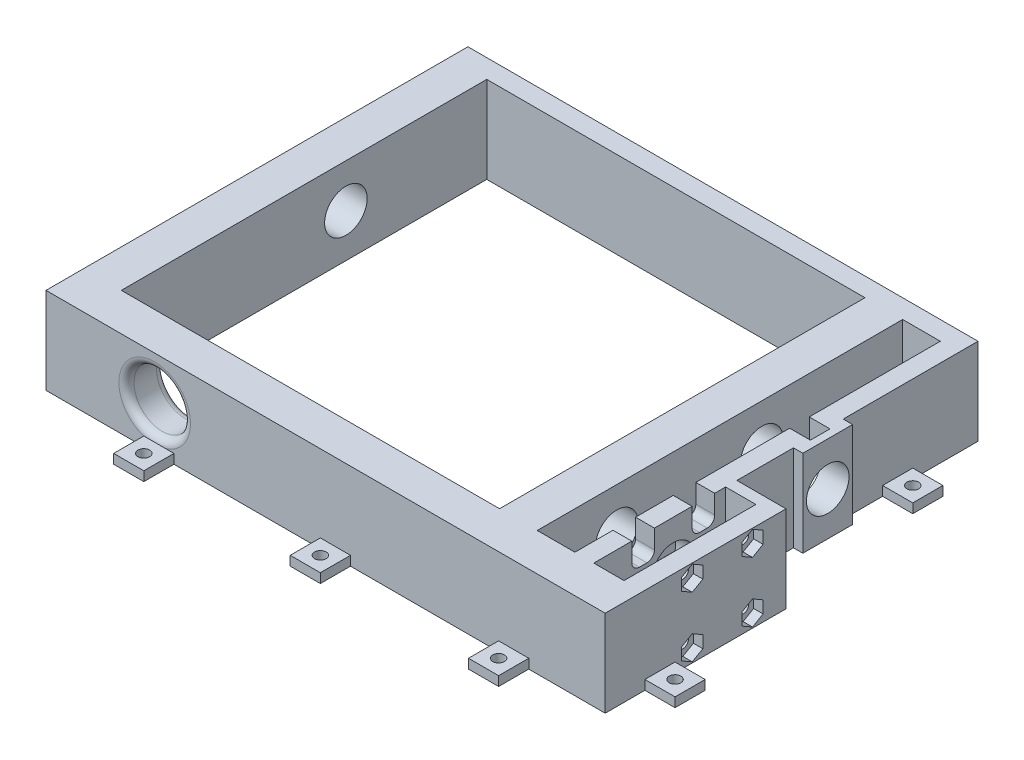
SolidWorks part; units mm, degrees
ref_plane "Front Plane" through (0, 0, 0) normal (0, 0, 1) x (1, 0, 0)
ref_plane "Top Plane" through (0, 0, 0) normal (0, 1, 0) x (1, 0, 0)
ref_plane "Right Plane" through (0, 0, 0) normal (1, 0, 0) x (0, 0, -1)
sketch "Sketch1" plane through (0, 0, 0) normal (0, 1, 0) x (1, 0, 0)
  line L0 (-50, -27.5) -> (-50, 27.5) construction
  line L1 (-40, -17.5) -> (40, -17.5) construction
  line L2 (-40, -17.5) -> (-40, 17.5) construction
  line L3 (-40, 17.5) -> (40, 17.5) construction
  line L4 (40, -17.5) -> (40, 17.5) construction
  line L5 (-40, -17.5) -> (40, 17.5) construction
  line L6 (-40, 17.5) -> (40, -17.5) construction
  line L7 (-50, 27.5) -> (50, 27.5) construction
  line L8 (50, -27.5) -> (50, 27.5) construction
  line L9 (-50, -27.5) -> (50, -27.5) construction
  line L10 (50, 0) -> (50.2, 0) construction
  line L11 (-50, 0) -> (-50.2, 0) construction
  line L12 (50.2, 0) -> (50.2, -27.5)
  line L13 (50.2, -27.5) -> (50.2, -47.5)
  line L14 (-50.2, 0) -> (-50.2, -27.5)
  line L15 (-50.2, -27.5) -> (-50.2, -47.5)
  line L16 (-50.2, -47.5) -> (50.2, -47.5)
  line L17 (50.2, 0) -> (50.2, 54.5)
  line L18 (-50.2, 0) -> (-50.2, 54.5)
  line L19 (-60.2, 0) -> (-60.2, 54.5)
  line L20 (-60.2, 0) -> (-60.2, -27.5)
  line L21 (-60.2, -27.5) -> (-60.2, -57.5)
  line L22 (-60.2, -57.5) -> (60.2, -57.5)
  line L23 (60.2, -27.5) -> (60.2, -57.5) construction
  line L24 (60.2, 0) -> (60.2, -27.5)
  line L25 (60.2, 0) -> (60.2, 54.5)
  line L26 (-50.2, 54.5) -> (-60.2, 54.5)
  line L27 (50.2, 54.5) -> (60.2, 54.5)
  line L28 (83.24, -47.5) -> (83.24, -9.5)
  line L29 (60.2, -57.5) -> (83.24, -57.5)
  line L31 (60.2, -47.5) -> (83.24, -47.5)
  line L32 (83.24, -57.5) -> (83.24, -47.5) construction
  line L33 (83.24, -57.5) -> (88.24, -57.5)
  line L34 (83.24, -57.5) -> (83.24, -9.5) construction
  line L35 (83.24, -9.5) -> (88.24, -9.5)
  line L36 (88.24, -57.5) -> (88.24, -9.5)
  line L37 (60.2, -47.5) -> (60.2, 54.5)
  line L39 (70.2, -47.5) -> (75.2, -47.5)
  line L40 (70.2, -47.5) -> (70.2, -9.5)
  line L41 (70.2, -9.5) -> (75.2, -9.5) construction
  line L42 (75.2, -47.5) -> (75.2, -9.5)
  line L43 (75.2, -9.5) -> (83.24, -9.5)
  line L44 (75.2, -9.5) -> (75.2, -12.5)
  line L45 (75.2, -12.5) -> (83.24, -12.5)
  line L46 (83.24, -9.5) -> (83.24, -12.5)
  line L47 (70.2, -9.5) -> (75.2, -9.5) construction
  line L48 (70.2, -9.5) -> (70.2, 54.5)
  line L49 (70.2, 54.5) -> (75.2, 54.5)
  line L50 (75.2, -9.5) -> (75.2, 54.5)
  line L51 (-50.2, 54.5) -> (50.2, 54.5)
  line L52 (-50.2, 54.5) -> (-50.2, 49.5)
  line L53 (-50.2, 49.5) -> (50.2, 49.5)
  line L54 (50.2, 54.5) -> (50.2, 49.5)
  line L55 (60.2, 54.5) -> (70.2, 54.5)
  line L56 (60.2, 54.5) -> (60.2, 49.5)
  line L57 (60.2, 49.5) -> (70.2, 49.5)
  line L58 (70.2, 54.5) -> (70.2, 49.5)
  point P0 (0, 0)
  point P10 (50, 0)
  point P11 (0, -27.5)
  point P12 (0, 27.5)
  point P13 (-50, 0)
  dimension "D1" = 80
  dimension "D2" = 35
  dimension "D4" = 0.2
  dimension "D5" = 20
  dimension "D7" = 8.04
  dimension "D8" = 5
  dimension "D9" = 10
  dimension "D10" = 5
  dimension "D11" = 38
  dimension "D12" = 3
  dimension "D13" = 22
  dimension "D14" = 5
  dimension "D3" = 10
  dimension "D6" = 10
extrude "Boss-Extrude1" add sketch "Sketch1" along normal mid plane 23 contours L31 L37 L24 L25 L27 L17 L12 L13 L16 L15 L14 L18 L26 L19 L20 L21 L22 L29 L33 L36 L35 L28 | L31 L42 L41 L40 | L42 L45 L28 L43 | L18 L53 L17 L51 | L37 L57 L48 L55
sketch "Sketch2" plane through (60.2, 0, 0) normal (1, 0, 0) x (0, 0, -1)
  line L4 (-47.5, -11.5) -> (49.5, -11.5)
  line L5 (49.5, -11.5) -> (49.5, 11.5)
  line L6 (-47.5, -11.5) -> (49.5, -11.5)
  line L7 (49.5, 11.5) -> (-47.5, 11.5)
  line L12 (49.5, -11.5) -> (49.5, 11.5)
  line L14 (49.5, 11.5) -> (-47.5, 11.5)
  line L15 (-47.5, 11.5) -> (-47.5, -11.5)
  line L16 (-47.5, 11.5) -> (-47.5, -11.5)
  circle A0 centre (12.106, 0) radius 5.65
  circle A1 centre (12.106, 0) radius 34.1 construction
  circle A4 centre (-26.394, 0) radius 5.65
  circle A5 centre (-26.394, 0) radius 4.4 construction
  dimension "D2" = 11.3
  dimension "D3" = 68.2
  dimension "D5" = 8.8
  dimension "D4" = 38.5
  dimension "D1" = 0
extrude "Cut-Extrude1" cut sketch "Sketch2" against normal up to surface (120.4 mm away) contours A0 up to face at (-60.2, 0, 1.5)
sketch "Sketch3" plane through (60.2, 0, 0) normal (1, 0, 0) x (0, 0, -1)
  circle A0 centre (-26.394, 0) radius 5.65 construction
  circle A1 centre (-26.394, 0) radius 5.65
extrude "Cut-Extrude2" cut sketch "Sketch3" against normal up to next
sketch "Sketch8" plane through (70.2, 0, 0) normal (-1, 0, 0) x (0, 0, 1)
  circle A0 centre (26.394, 0) radius 5.65 construction
  circle A1 centre (26.394, 0) radius 5.65
extrude "Cut-Extrude5" cut sketch "Sketch8" against normal up to surface (5 mm away) up to face at (75.2, 0, 30)
sketch "Sketch10" plane through (83.24, 0, 0) normal (-1, 0, 0) x (0, 0, 1)
  line L1 (18.394, -8) -> (34.394, -8) construction
  line L2 (18.394, -8) -> (18.394, 8) construction
  line L3 (18.394, 8) -> (34.394, 8) construction
  line L4 (34.394, -8) -> (34.394, 8) construction
  line L5 (18.394, -8) -> (34.394, 8) construction
  line L6 (18.394, 8) -> (34.394, -8) construction
  circle A0 centre (26.394, 0) radius 5.65 construction
  circle A1 centre (26.394, 0) radius 5.65 construction
  circle A2 centre (18.394, 8) radius 1.8
  circle A3 centre (34.394, -8) radius 1.8
  circle A4 centre (18.394, -8) radius 1.8
  circle A5 centre (34.394, 8) radius 1.8
  dimension "D2" = 3.6
  dimension "D1" = 16
extrude "Boss-Extrude4" add sketch "Sketch10" along normal blind 1
sketch "Sketch11" plane through (82.24, 0, 0) normal (-1, 0, 0) x (0, 0, 1)
  circle A0 centre (18.394, 8) radius 1.5
  circle A1 centre (34.394, 8) radius 1.5
  circle A2 centre (34.394, -8) radius 1.5
  circle A3 centre (18.394, -8) radius 1.5
  dimension "D1" = 3
extrude "Cut-Extrude6" cut sketch "Sketch11" against normal up to surface (6 mm away) up to face at (88.24, 0, 33.5)
sketch "Sketch12" plane through (88.24, 0, 0) normal (1, 0, 0) x (0, 0, -1)
  line L1 (-31.594, 9.6166) -> (-34.394, 11.2332)
  line L2 (-34.394, 11.2332) -> (-37.194, 9.6166)
  line L3 (-37.194, 9.6166) -> (-37.194, 6.3834)
  line L4 (-57.5, -11.5) -> (-9.5, -11.5)
  line L5 (-9.5, -11.5) -> (-9.5, 11.5)
  line L6 (-9.5, 11.5) -> (-57.5, 11.5)
  line L7 (-57.5, 11.5) -> (-57.5, -11.5)
  line L8 (-57.5, -11.5) -> (-9.5, -11.5)
  line L10 (-9.5, 11.5) -> (-57.5, 11.5)
  line L12 (-37.194, 6.3834) -> (-34.394, 4.7668)
  line L13 (-34.394, 4.7668) -> (-31.594, 6.3834)
  line L14 (-31.594, 6.3834) -> (-31.594, 9.6166)
  line L15 (-18.394, 11.2332) -> (-21.194, 9.6166)
  line L16 (-21.194, 9.6166) -> (-21.194, 6.3834)
  line L17 (-21.194, 6.3834) -> (-18.394, 4.7668)
  line L18 (-18.394, 4.7668) -> (-15.594, 6.3834)
  line L19 (-15.594, 6.3834) -> (-15.594, 9.6166)
  line L20 (-15.594, 9.6166) -> (-18.394, 11.2332)
  line L21 (-31.594, -6.3834) -> (-34.394, -4.7668)
  line L22 (-34.394, -4.7668) -> (-37.194, -6.3834)
  line L23 (-37.194, -6.3834) -> (-37.194, -9.6166)
  line L24 (-37.194, -9.6166) -> (-34.394, -11.2332)
  line L25 (-34.394, -11.2332) -> (-31.594, -9.6166)
  line L26 (-31.594, -9.6166) -> (-31.594, -6.3834)
  line L27 (-15.594, -6.3834) -> (-18.394, -4.7668)
  line L28 (-18.394, -4.7668) -> (-21.194, -6.3834)
  line L29 (-21.194, -6.3834) -> (-21.194, -9.6166)
  line L30 (-21.194, -9.6166) -> (-18.394, -11.2332)
  line L31 (-18.394, -11.2332) -> (-15.594, -9.6166)
  line L32 (-15.594, -9.6166) -> (-15.594, -6.3834)
  line L36 (-9.5, -11.5) -> (-9.5, 11.5)
  line L38 (-57.5, 11.5) -> (-57.5, -11.5)
  circle A0 centre (-34.394, 8) radius 2.8 construction
  circle A1 centre (-18.394, 8) radius 2.8 construction
  circle A2 centre (-34.394, -8) radius 2.8 construction
  circle A3 centre (-18.394, -8) radius 2.8 construction
  circle M5 centre (-18.394, -8) radius 1.5
  circle M6 centre (-34.394, -8) radius 1.5
  circle M7 centre (-34.394, 8) radius 1.5
  circle M8 centre (-18.394, 8) radius 1.5
  line M11 (-9.5, 11.5) -> (-57.5, 11.5)
  dimension "D2" = 5.6
  dimension "D1" = 0
extrude "Cut-Extrude7" cut sketch "Sketch12" against normal blind 2.5 contours L13 L14 L1 L2 L3 L12 M11 M7 | L19 L20 L10 L15 L16 L17 L18 M8 | L31 L32 L27 L28 L29 L30 L8 M5 | L25 L26 L21 L22 L23 L24 L8 M6
sketch "Sketch13" plane through (75.2, 0, 0) normal (1, 0, 0) x (0, 0, -1)
  line L0 (-57.5, 11.5) -> (-9.5, 11.5) construction
  line L1 (-35.394, 4.5) -> (-33.394, 4.5)
  line L2 (-37.394, 6.5) -> (-37.394, 11.5)
  line L3 (-37.394, 11.5) -> (-31.394, 11.5)
  line L4 (-31.394, 6.5) -> (-31.394, 11.5)
  line L5 (-37.394, 4.5) -> (-31.394, 11.5) construction
  line L6 (-37.394, 11.5) -> (-31.394, 4.5) construction
  line L7 (-19.394, 4.5) -> (-17.394, 4.5)
  line L8 (-21.394, 6.5) -> (-21.394, 11.5)
  line L9 (-21.394, 11.5) -> (-15.394, 11.5)
  line L10 (-15.394, 6.5) -> (-15.394, 11.5)
  line L11 (-21.394, 4.5) -> (-15.394, 11.5) construction
  line L12 (-21.394, 11.5) -> (-15.394, 4.5) construction
  line L13 (-21.394, -11.5) -> (-15.394, -11.5)
  line L14 (-21.394, -11.5) -> (-21.394, -6.5)
  line L15 (-19.394, -4.5) -> (-17.394, -4.5)
  line L16 (-15.394, -11.5) -> (-15.394, -6.5)
  line L17 (-21.394, -11.5) -> (-15.394, -4.5) construction
  line L18 (-21.394, -4.5) -> (-15.394, -11.5) construction
  line L19 (-37.394, -11.5) -> (-31.394, -11.5)
  line L20 (-37.394, -11.5) -> (-37.394, -6.5)
  line L21 (-35.394, -4.5) -> (-33.394, -4.5)
  line L22 (-31.394, -11.5) -> (-31.394, -6.5)
  line L23 (-37.394, -11.5) -> (-31.394, -4.5) construction
  line L24 (-37.394, -4.5) -> (-31.394, -11.5) construction
  line L25 (-57.5, -11.5) -> (-9.5, -11.5) construction
  circle A0 centre (-34.394, -8) radius 1.5 construction
  circle A1 centre (-18.394, -8) radius 1.5 construction
  circle A2 centre (-18.394, 8) radius 1.5 construction
  circle A3 centre (-34.394, 8) radius 1.5 construction
  circle A4 centre (-34.394, -8) radius 1.5 construction
  circle A5 centre (-18.394, -8) radius 1.5 construction
  circle A6 centre (-18.394, 8) radius 1.5 construction
  circle A7 centre (-34.394, 8) radius 1.5 construction
  arc A8 (-17.394, -4.5) -> (-15.394, -6.5) centre (-17.394, -6.5) cw
  arc A9 (-21.394, -6.5) -> (-19.394, -4.5) centre (-19.394, -6.5) cw
  arc A10 (-33.394, -4.5) -> (-31.394, -6.5) centre (-33.394, -6.5) cw
  arc A11 (-37.394, -6.5) -> (-35.394, -4.5) centre (-35.394, -6.5) cw
  arc A12 (-17.394, 4.5) -> (-15.394, 6.5) centre (-17.394, 6.5) ccw
  arc A13 (-19.394, 4.5) -> (-21.394, 6.5) centre (-19.394, 6.5) cw
  arc A14 (-33.394, 4.5) -> (-31.394, 6.5) centre (-33.394, 6.5) ccw
  arc A15 (-35.394, 4.5) -> (-37.394, 6.5) centre (-35.394, 6.5) cw
  point P6 (-34.394, 8)
  point P22 (0, 0)
  point P23 (-18.394, 8)
  point P28 (-18.394, -8)
  point P33 (-34.394, -8)
  point P36 (-34.394, 8)
  point P37 (0, 0)
  dimension "D2" = 2
  dimension "D1" = 6
extrude "Cut-Extrude9" cut sketch "Sketch13" against normal up to surface (5 mm away) up to face at (70.2, 0, 32.044)
sketch "Sketch14" plane through (70.2, 0, 0) normal (-1, 0, 0) x (0, 0, 1)
  line L0 (15.394, 11.5) -> (-49.5, 11.5) construction
  line L1 (-14.706, 5.0162) -> (-9.506, 5.0162)
  line L2 (-14.706, 5.0162) -> (-14.706, 11.5)
  line L3 (-14.706, 11.5) -> (-9.506, 11.5)
  line L4 (-9.506, 5.0162) -> (-9.506, 11.5)
  circle A0 centre (-12.106, 0) radius 5.65 construction
  circle A1 centre (-12.106, 0) radius 5.65
  line M13 (15.394, 11.5) -> (-49.5, 11.5)
  dimension "D1" = 5.2
extrude "Cut-Extrude10" cut sketch "Sketch14" against normal up to next contours L1 A1 | A1 L4 L2 M13 | L1 A1
sketch "Sketch15" plane through (0, 0, 57.5) normal (0, 0, 1) x (1, 0, 0)
  line L5 (-60.2, -11.5) -> (88.24, -11.5) construction
  line L6 (-34.3437, -11.5) -> (-28.3437, -11.5)
  circle A0 centre (-31.3437, 0) radius 7.5
  dimension "D3" = 15
extrude "Cut-Extrude11" cut sketch "Sketch15" against normal up to surface (10 mm away) contours A0 up to face at (0, 0, 47.5)
fillet "Fillet1" radius 2 2 edges at (-38.8437, 0, 47.5) (-23.8437, 0, 57.5)
sketch "Sketch16" plane through (0, -11.5, 0) normal (0, -1, 0) x (1, 0, 0)
  line L0 (-60.2, 57.5) -> (-60.2, -54.5) construction
  line L1 (-60.2, -54.5) -> (75.2, -54.5) construction
  line L2 (75.2, 9.5) -> (75.2, -54.5) construction
  line L3 (88.24, 57.5) -> (88.24, 9.5) construction
  line L4 (-60.2, 57.5) -> (88.24, 57.5) construction
  line L6 (-26.235, 57.5) -> (-34.235, 57.5)
  line L7 (-26.235, 57.5) -> (-26.235, 65.5)
  line L8 (-26.235, 65.5) -> (-34.235, 65.5)
  line L9 (-34.235, 57.5) -> (-34.235, 65.5)
  line L10 (-60.2, 44.1008) -> (-68.2, 44.1008)
  line L11 (-60.2, 44.1008) -> (-60.2, 36.1008)
  line L12 (-60.2, 36.1008) -> (-68.2, 36.1008)
  line L13 (-68.2, 44.1008) -> (-68.2, 36.1008)
  line L14 (-60.2, -36.5827) -> (-68.2, -36.5827)
  line L15 (-60.2, -36.5827) -> (-60.2, -44.5827)
  line L16 (-60.2, -44.5827) -> (-68.2, -44.5827)
  line L17 (-68.2, -36.5827) -> (-68.2, -44.5827)
  line L18 (-36.4203, -54.5) -> (-28.4203, -54.5)
  line L19 (-36.4203, -54.5) -> (-36.4203, -62.5)
  line L20 (-36.4203, -62.5) -> (-28.4203, -62.5)
  line L21 (-28.4203, -54.5) -> (-28.4203, -62.5)
  line L22 (-5.3881, -54.5) -> (2.6119, -54.5)
  line L23 (-5.3881, -54.5) -> (-5.3881, -62.5)
  line L24 (-5.3881, -62.5) -> (2.6119, -62.5)
  line L25 (2.6119, -54.5) -> (2.6119, -62.5)
  line L26 (46.8273, -54.5) -> (54.8273, -54.5)
  line L27 (46.8273, -54.5) -> (46.8273, -62.5)
  line L28 (46.8273, -62.5) -> (54.8273, -62.5)
  line L29 (54.8273, -54.5) -> (54.8273, -62.5)
  line L30 (75.2, -37.1824) -> (83.2, -37.1824)
  line L31 (75.2, -37.1824) -> (75.2, -29.1824)
  line L32 (75.2, -29.1824) -> (83.2, -29.1824)
  line L33 (83.2, -37.1824) -> (83.2, -29.1824)
  line L38 (88.24, 38.9621) -> (96.24, 38.9621)
  line L39 (88.24, 38.9621) -> (88.24, 46.9621)
  line L40 (88.24, 46.9621) -> (96.24, 46.9621)
  line L41 (96.24, 38.9621) -> (96.24, 46.9621)
  line L42 (67.9476, 57.5) -> (59.9476, 57.5)
  line L43 (67.9476, 57.5) -> (67.9476, 65.5)
  line L44 (67.9476, 65.5) -> (59.9476, 65.5)
  line L45 (59.9476, 57.5) -> (59.9476, 65.5)
  line L46 (20.6236, 57.5) -> (12.6236, 57.5)
  line L47 (20.6236, 57.5) -> (20.6236, 65.5)
  line L48 (20.6236, 65.5) -> (12.6236, 65.5)
  line L49 (12.6236, 57.5) -> (12.6236, 65.5)
  circle A0 centre (-30.235, 61.5) radius 1.55
  circle A1 centre (16.6236, 61.5) radius 1.55
  circle A2 centre (63.9476, 61.5) radius 1.55
  circle A3 centre (92.24, 42.9621) radius 1.55
  circle A5 centre (79.2, -33.1824) radius 1.55
  circle A6 centre (50.8273, -58.5) radius 1.55
  circle A7 centre (-1.3881, -58.5) radius 1.55
  circle A8 centre (-32.4203, -58.5) radius 1.55
  circle A9 centre (-64.2, -40.5827) radius 1.55
  circle A10 centre (-64.2, 40.1008) radius 1.55
  point P0 (-60.2, 41.1522)
  point P1 (-60.2, -39.1219)
  point P4 (-32.9592, -54.5)
  point P5 (1.1977, -54.5)
  point P8 (48.3924, -54.5)
  point P9 (75.2, -40.7382)
  point P10 (79.2, -37.1824)
  point P13 (88.24, 41.1522)
  point P14 (65.848, 57.5)
  point P17 (18.761, 57.5)
  point P20 (-30.5887, 57.5)
  point P49 (0, 0)
  point P50 (0, 0)
  point P51 (83.2, -33.1824)
  point P65 (-30.235, 65.5)
  point P66 (-30.235, 61.5)
  point P67 (16.6236, 61.5)
  point P68 (63.9476, 61.5)
  point P69 (-64.2, 40.1008)
  point P70 (-64.2, -40.5827)
  point P71 (-32.4203, -58.5)
  point P72 (-1.3881, -58.5)
  point P73 (50.8273, -58.5)
  point P74 (79.2, -33.1824)
  point P76 (92.24, 42.9621)
  dimension "D2" = 3.1
  dimension "D1" = 8
extrude "Boss-Extrude5" add sketch "Sketch16" against normal blind 2.5 separate body
sketch "Sketch17" plane through (75.2, 0, 0) normal (1, 0, 0) x (0, 0, -1)
  line L0 (14.706, 11.5) -> (54.5, 11.5) construction
  line L1 (5.506, -11.5) -> (18.706, -11.5)
  line L2 (5.506, -11.5) -> (5.506, 11.5)
  line L3 (5.506, 11.5) -> (18.706, 11.5)
  line L4 (18.706, -11.5) -> (18.706, 11.5)
  line L5 (5.506, -11.5) -> (18.706, 11.5) construction
  line L6 (5.506, 11.5) -> (18.706, -11.5) construction
  arc A0 (9.506, 5.0162) -> (14.706, 5.0162) centre (12.106, 0) ccw construction
  arc A1 (9.506, 5.0162) -> (14.706, 5.0162) centre (12.106, 0) ccw construction
  circle A2 centre (12.106, 0) radius 5.65
  dimension "D2" = 11.3
  dimension "D1" = 13.2
extrude "Boss-Extrude6" add sketch "Sketch17" along normal blind 2.5
sketch "Sketch18" plane through (75.2, 0, 0) normal (-1, 0, 0) x (0, 0, 1)
  line L3 (-9.506, 11.5) -> (-14.706, 11.5)
  line L4 (-14.706, 11.5) -> (-14.706, 5.0162)
  line L5 (-9.506, 5.0162) -> (-9.506, 11.5)
  line L6 (-9.506, 11.5) -> (-14.706, 11.5)
  line L7 (-14.706, 11.5) -> (-14.706, 5.0162)
  line L8 (-9.506, 5.0162) -> (-9.506, 11.5)
  arc A1 (-9.506, 5.0162) -> (-14.706, 5.0162) centre (-12.106, 0) ccw
  arc A4 (-9.506, 5.0162) -> (-14.706, 5.0162) centre (-12.106, 0) ccw
  dimension "D1" = 0
extrude "Cut-Extrude12" cut sketch "Sketch18" against normal blind 0.5
equation "\"a\"= 1"
equation "\"b\"= 1"
equation "\"c\"= 1"
equation "\"d\"= 1"
equation "\"e\"= 1"
equation "\"x\"= 1"
equation "\"y\"= 1"
equation "\"z\"= 1"
